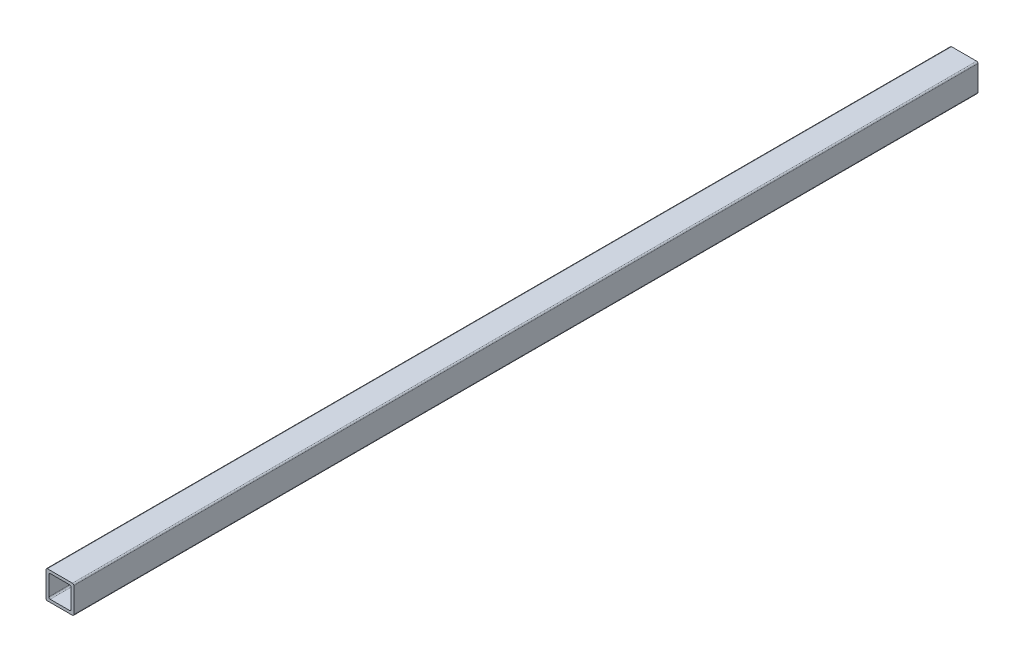
SolidWorks part; units mm, degrees
ref_plane "Plan de face" through (0, 0, 0) normal (0, 0, 1) x (1, 0, 0)
ref_plane "Plan de dessus" through (0, 0, 0) normal (0, 1, 0) x (1, 0, 0)
ref_plane "Plan de droite" through (0, 0, 0) normal (1, 0, 0) x (0, 0, -1)
sketch "Esquisse2" plane through (0, 0, 0) normal (0, 0, 1) x (1, 0, 0)
  line L0 (6, 4) -> (34, 4)
  line L1 (2, 0) -> (38, 0)
  line L2 (0, 2) -> (0, 38)
  line L3 (2, 40) -> (38, 40)
  line L4 (40, 2) -> (40, 38)
  line L5 (36, 6) -> (36, 34)
  line L6 (6, 36) -> (34, 36)
  line L7 (4, 6) -> (4, 34)
  line L8 (4, 4) -> (36, 4) construction
  line L9 (36, 4) -> (36, 36) construction
  line L10 (4, 36) -> (36, 36) construction
  line L11 (4, 4) -> (4, 36) construction
  line L12 (0, 0) -> (40, 0) construction
  line L13 (0, 0) -> (0, 40) construction
  line L14 (0, 40) -> (40, 40) construction
  line L15 (40, 0) -> (40, 40) construction
  arc A0 (34, 4) -> (36, 6) centre (34, 6) ccw
  arc A1 (36, 34) -> (34, 36) centre (34, 34) ccw
  arc A2 (6, 36) -> (4, 34) centre (6, 34) ccw
  arc A3 (4, 6) -> (6, 4) centre (6, 6) ccw
  arc A4 (2, 0) -> (0, 2) centre (2, 2) cw
  arc A5 (0, 38) -> (2, 40) centre (2, 38) cw
  arc A6 (38, 40) -> (40, 38) centre (38, 38) cw
  arc A7 (40, 2) -> (38, 0) centre (38, 2) cw
  point P24 (0, 0)
  dimension "D4" = 2
  dimension "D1" = 40
  dimension "D2" = 40
  dimension "D3" = 4
extrude "Boss.-Extru.1" add sketch "Esquisse2" along normal blind 1300
